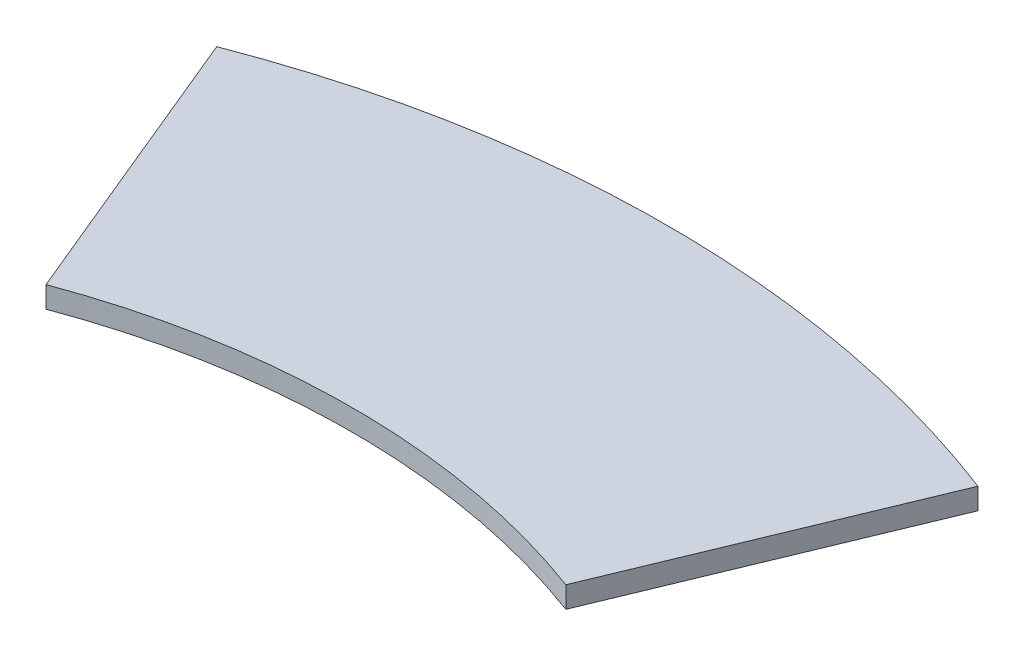
SolidWorks part; units mm, degrees
material "Chrome Stainless Steel"
ref_plane "Front Plane" through (0, 0, 0) normal (0, 0, 1) x (1, 0, 0)
ref_plane "Top Plane" through (0, 0, 0) normal (0, 1, 0) x (1, 0, 0)
ref_plane "Right Plane" through (0, 0, 0) normal (1, 0, 0) x (0, 0, -1)
sketch "Sketch1" plane through (0, 0, 0) normal (0, 1, 0) x (1, 0, 0)
  line L0 (0, 48.6024) -> (0, -42.7051) construction
  line L1 (-179.3899, 52.9653) -> (-121.9629, -85.6757) construction
  line L2 (123.1831, -85.6757) -> (180.6101, 52.9653) construction
  line L3 (-178.0735, 52.4003) -> (-121.4081, -84.4021)
  line L4 (122.6282, -84.4021) -> (179.2936, 52.4003)
  arc A0 (-121.9629, -85.6757) -> (123.1831, -85.6757) centre (0.6101, -413.5108) cw construction
  arc A1 (180.6101, 52.9653) -> (-179.3899, 52.9653) centre (0.6101, -413.5108) ccw construction
  arc A2 (-121.4081, -84.4021) -> (122.6282, -84.4021) centre (0.6101, -413.5108) cw
  arc A3 (179.2936, 52.4003) -> (-178.0735, 52.4003) centre (0.6101, -413.5108) ccw
  dimension "D1" = 1
extrude "Boss-Extrude1" add sketch "Sketch1" along normal mid plane 10
